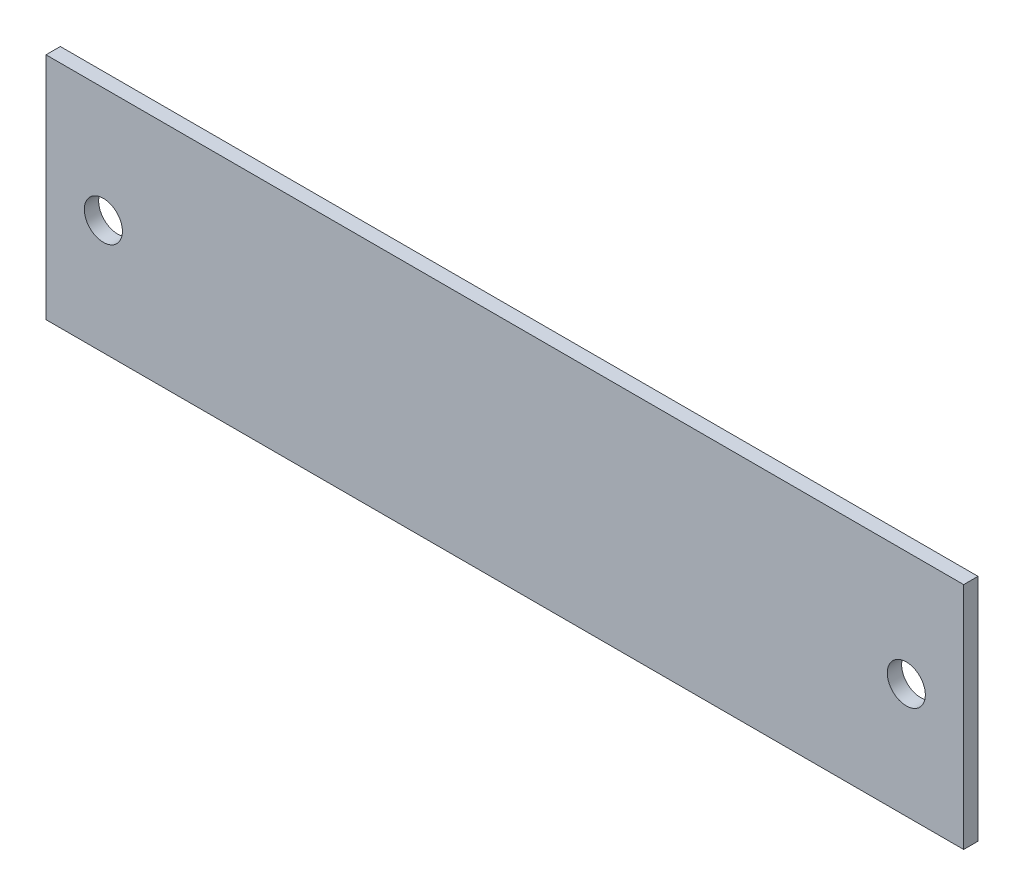
SolidWorks part; units mm, degrees
material "ABS"
ref_plane "Front Plane" through (0, 0, 0) normal (0, 0, 1) x (1, 0, 0)
ref_plane "Top Plane" through (0, 0, 0) normal (0, 1, 0) x (1, 0, 0)
ref_plane "Right Plane" through (0, 0, 0) normal (1, 0, 0) x (0, 0, -1)
sketch "Sketch1" plane through (0, 0, 0) normal (0, 0, 1) x (1, 0, 0)
  line L0 (-44.45, 0) -> (44.45, 0) construction
  line L1 (50.8, -12.7) -> (-50.8, -12.7)
  line L2 (50.8, -12.7) -> (50.8, 12.7)
  line L3 (50.8, 12.7) -> (-50.8, 12.7)
  line L4 (-50.8, -12.7) -> (-50.8, 12.7)
  line L5 (50.8, -12.7) -> (-50.8, 12.7) construction
  line L6 (50.8, 12.7) -> (-50.8, -12.7) construction
  circle A0 centre (-44.45, 0) radius 2.1082
  circle A1 centre (44.45, 0) radius 2.1082
  point P0 (0, 0)
  dimension "D4" = 4.2164
  dimension "D1" = 88.9
  dimension "D2" = 101.6
  dimension "D3" = 25.4
extrude "Boss-Extrude1" add sketch "Sketch1" along normal blind 1.5875
